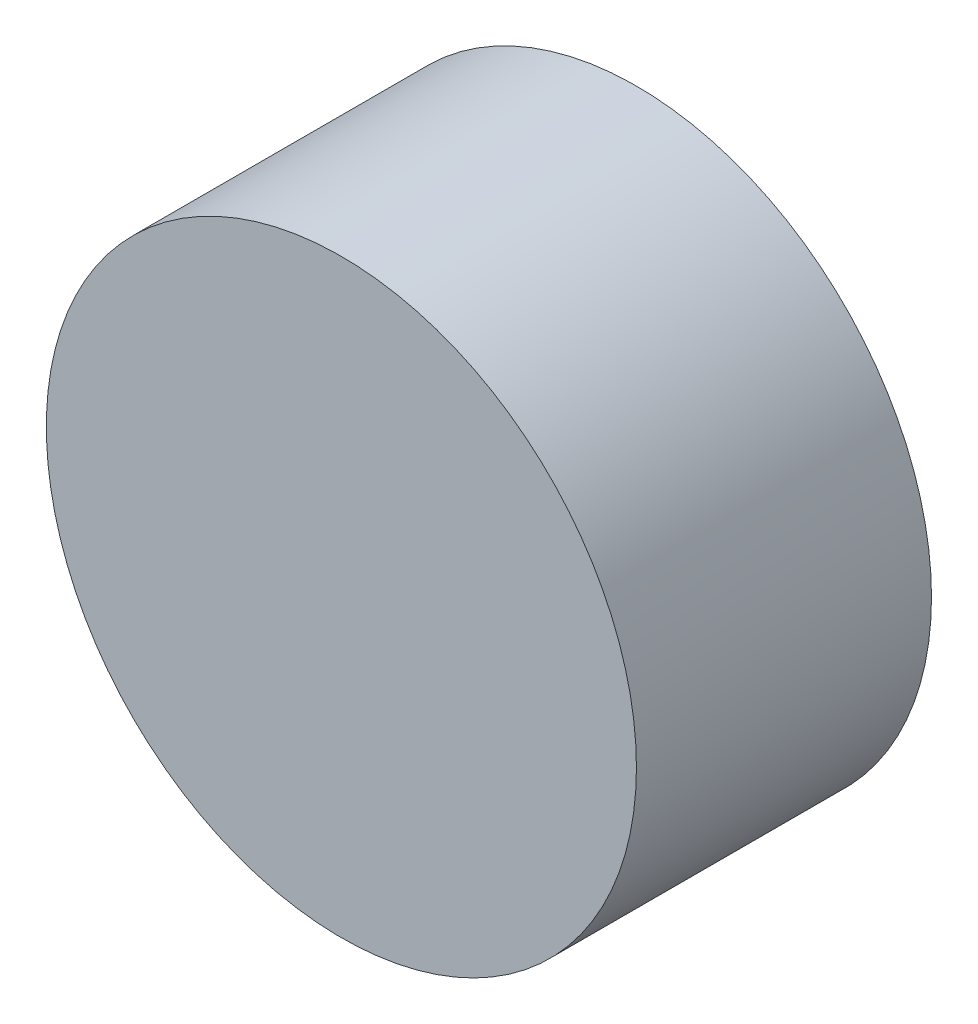
SolidWorks part; units mm, degrees
ref_plane "Alzado" through (0, 0, 0) normal (0, 0, 1) x (1, 0, 0)
ref_plane "Planta" through (0, 0, 0) normal (0, 1, 0) x (1, 0, 0)
ref_plane "Vista lateral" through (0, 0, 0) normal (1, 0, 0) x (0, 0, -1)
sketch "Croquis1" plane through (0, 0, 0) normal (0, 0, 1) x (1, 0, 0)
  circle A0 centre (0, 0) radius 10
  dimension "D1" = 20
extrude "Saliente-Extruir1" add sketch "Croquis1" along normal blind 10
